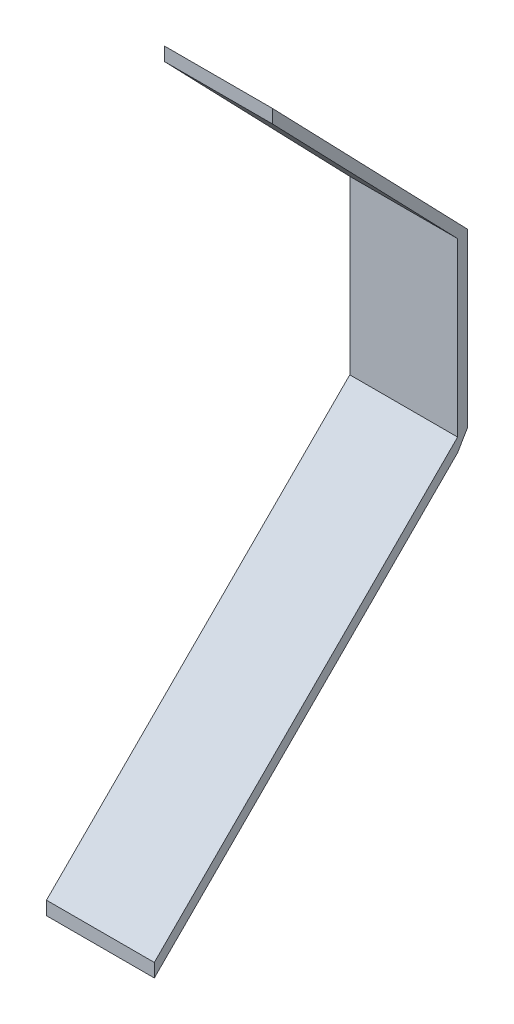
SolidWorks part; units mm, degrees
ref_plane "Front" through (0, 0, 0) normal (0, 0, 1) x (1, 0, 0)
ref_plane "Top" through (0, 0, 0) normal (0, 1, 0) x (1, 0, 0)
ref_plane "Right" through (0, 0, 0) normal (1, 0, 0) x (0, 0, -1)
sketch "草图3" plane through (0, 0, 0) normal (1, 0, 0) x (0, 0, -1)
  line L0 (0, 0) -> (84.7721, 0) construction
  line L1 (0, 0) -> (0, 476.3524) construction
  line L2 (0, 4) -> (0, 0)
  line L3 (35, -11.0952) -> (35, 248.9048) construction
  line L4 (-47.1332, 202) -> (87.3249, 202) construction
  line L5 (90, -54.2619) -> (90, 256.1429) construction
  line L6 (0, 0) -> (90, 90)
  line L7 (0, 4) -> (90, 94)
  line L8 (35, 202) -> (90, 145)
  line L9 (90, 145) -> (90, 94)
  line L10 (35, 202) -> (35, 206)
  line L11 (35, 206) -> (90, 149)
  line L12 (90, 149) -> (92.9372, 145.956)
  line L13 (90, 90) -> (92.9372, 94.956)
  line L14 (92.9372, 94.956) -> (92.9372, 145.956)
  dimension "D1" = 35
  dimension "D2" = 202
  dimension "D3" = 260
  dimension "D4" = 90
  dimension "D5" = 4
  dimension "D6" = 4
extrude "凸台-拉伸1" add sketch "草图3" along normal blind 32
